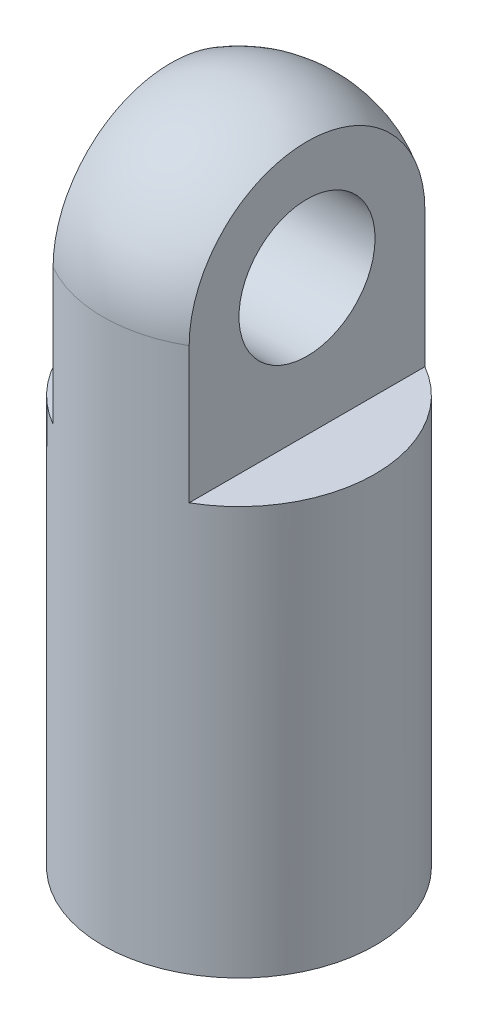
SolidWorks part; units mm, degrees
ref_plane "前视基准面" through (0, 0, 0) normal (0, 0, 1) x (1, 0, 0)
ref_plane "上视基准面" through (0, 0, 0) normal (0, 1, 0) x (1, 0, 0)
ref_plane "右视基准面" through (0, 0, 0) normal (1, 0, 0) x (0, 0, -1)
other "Configuration Table"
sketch "草图1" plane through (0, 0, 0) normal (0, 1, 0) x (1, 0, 0)
  circle A0 centre (0, 0) radius 8
  dimension "D1" = 16
extrude "凸台-拉伸1" add sketch "草图1" along normal blind 32
sketch "草图2" plane through (0, 32, 0) normal (0, 1, 0) x (1, 0, 0)
  line L0 (-1000.0537, 0) -> (48999.9463, 0) construction
ref_plane "基准面1" through (0, 0, 0) normal (0, 0, 1) x (1, 0, 0)
sketch "草图3" plane through (0, 0, 0) normal (0, 0, 1) x (1, 0, 0)
  line L0 (-201000.0537, 32) -> (248999.9463, 32) construction
  line L1 (8, 32) -> (-8, 32) construction
  line L2 (0, 32) -> (0, 44.3425) construction
  line L3 (0, 40) -> (0, 24)
  circle A0 centre (0, 32) radius 8
  point P7 (-8, 32)
revolve "旋转4" add sketch "草图3" angle 360 about L2
ref_plane "基准面2" through (0, 40, 0) normal (0, 1, 0) x (1, 0, 0)
sketch "草图5" plane through (0, 40, 0) normal (0, 1, 0) x (1, 0, 0)
  line L0 (4, -6.9282) -> (4, 6.9282)
  line L2 (0, -0.1179) -> (0, 49999.8821) construction
  line L3 (-4, -6.9282) -> (-4, 6.9282)
  arc A0 (-4, 6.9282) -> (-4, -6.9282) centre (0, 0) ccw
  circle A1 centre (0, 0) radius 8 construction
  arc A2 (4, -6.9282) -> (4, 6.9282) centre (0, 0) ccw
  point P5 (-4, 6.9282)
  dimension "D1" = 8
extrude "切除-拉伸1" cut sketch "草图5" against normal blind 16
sketch "草图6" plane through (4, 0, 0) normal (1, 0, 0) x (0, 0, -1)
  line L0 (0, 27500) -> (0, -27500) construction
  circle A0 centre (0, 32) radius 4
  dimension "D1" = 8
extrude "切除-拉伸2" cut sketch "草图6" against normal through all
